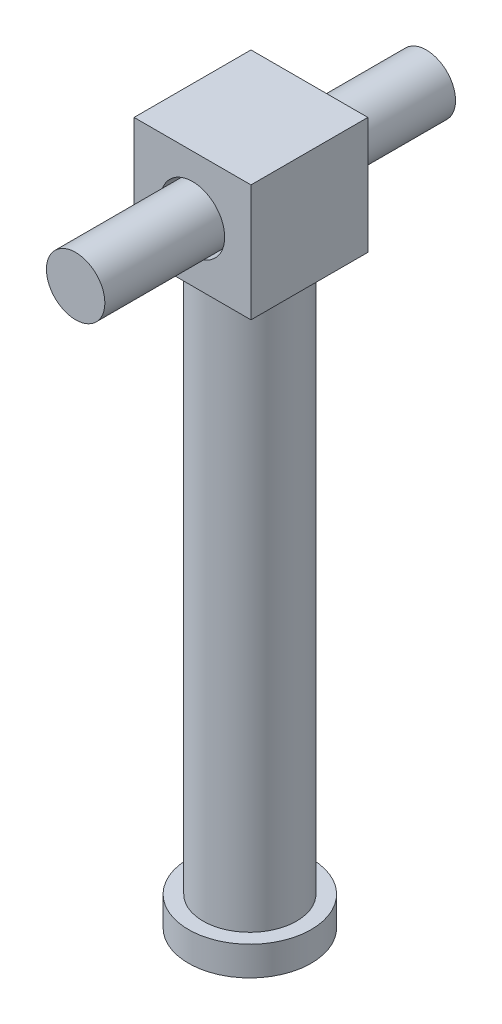
SolidWorks part; units mm, degrees
ref_plane "Front Plane" through (0, 0, 0) normal (0, 0, 1) x (1, 0, 0)
ref_plane "Top Plane" through (0, 0, 0) normal (0, 1, 0) x (1, 0, 0)
ref_plane "Right Plane" through (0, 0, 0) normal (1, 0, 0) x (0, 0, -1)
sketch "Sketch1" plane through (0, 0, 0) normal (0, 1, 0) x (1, 0, 0)
  circle A0 centre (0, -0.3887) radius 16
  dimension "D1" = 32
extrude "Boss-Extrude1" add sketch "Sketch1" along normal blind 100
sketch "Sketch2" plane through (0, 100, 0) normal (0, 1, 0) x (1, 0, 0)
  line L1 (-20, -20) -> (20, -20)
  line L2 (-20, -20) -> (-20, 20)
  line L3 (-20, 20) -> (20, 20)
  line L4 (20, -20) -> (20, 20)
  line L5 (-20, -20) -> (20, 20) construction
  line L6 (-20, 20) -> (20, -20) construction
  point P0 (0, 0)
  dimension "D1" = 40
  dimension "D2" = 40
extrude "Boss-Extrude2" add sketch "Sketch2" along normal blind 40
sketch "Sketch3" plane through (0, 0, 20) normal (0, 0, 1) x (1, 0, 0)
  circle A0 centre (0, 120) radius 10
extrude "Boss-Extrude3" add sketch "Sketch3" along normal blind 40 and the other way blind 80
sketch "Sketch4" plane through (0, 0, 0) normal (0, -1, 0) x (1, 0, 0)
  circle A0 centre (0, 0.3887) radius 16
extrude "Boss-Extrude4" add sketch "Sketch4" along normal blind 100
sketch "Sketch5" plane through (0, -100, 0) normal (0, -1, 0) x (1, 0, 0)
  circle A0 centre (0, 0.3887) radius 16
  circle A1 centre (0, 0.3887) radius 21
  dimension "D1" = 5
extrude "Boss-Extrude5" add sketch "Sketch5" against normal blind 10
sketch "Sketch6" plane through (0, 0, 60) normal (0, 0, 1) x (1, 0, 0)
  circle A0 centre (0, 120) radius 10
  circle A1 centre (0, 120) radius 11
  dimension "D1" = 1
extrude "Cut-Extrude1" cut sketch "Sketch6" against normal blind 100
